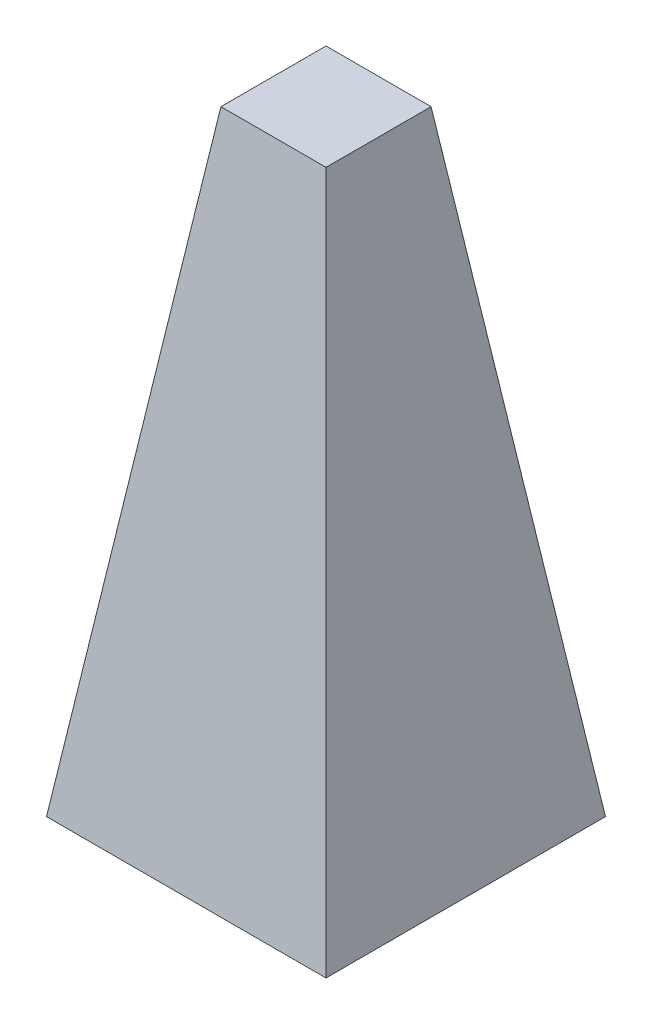
SolidWorks part; units mm, degrees
ref_plane "Front Plane" through (0, 0, 0) normal (0, 0, 1) x (1, 0, 0)
ref_plane "Top Plane" through (0, 0, 0) normal (0, 1, 0) x (1, 0, 0)
ref_plane "Right Plane" through (0, 0, 0) normal (1, 0, 0) x (0, 0, -1)
sketch "Sketch1" plane through (0, 0, 0) normal (0, 1, 0) x (1, 0, 0)
  line L1 (-63.5, -63.5) -> (63.5, -63.5)
  line L2 (-63.5, -63.5) -> (-63.5, 63.5)
  line L3 (-63.5, 63.5) -> (63.5, 63.5)
  line L4 (63.5, -63.5) -> (63.5, 63.5)
  line L5 (-63.5, -63.5) -> (63.5, 63.5) construction
  line L6 (-63.5, 63.5) -> (63.5, -63.5) construction
  point P0 (0, 0)
  point P6 (0, 0)
  point P7 (0, 0)
  point P8 (0, 0)
  dimension "D1" = 127
ref_plane "Plane1" through (0, 279.4, 0) normal (0, 1, 0) x (1, 0, 0)
sketch "Sketch2" plane through (0, 279.4, 0) normal (0, 1, 0) x (1, 0, 0)
  line L1 (-23.876, -23.876) -> (23.876, -23.876)
  line L2 (-23.876, -23.876) -> (-23.876, 23.876)
  line L3 (-23.876, 23.876) -> (23.876, 23.876)
  line L4 (23.876, -23.876) -> (23.876, 23.876)
  line L5 (-23.876, -23.876) -> (23.876, 23.876) construction
  line L6 (-23.876, 23.876) -> (23.876, -23.876) construction
  point P0 (0, 0)
  dimension "D1" = 47.752
loft "Loft1" add profiles "Sketch1", "Sketch2"
